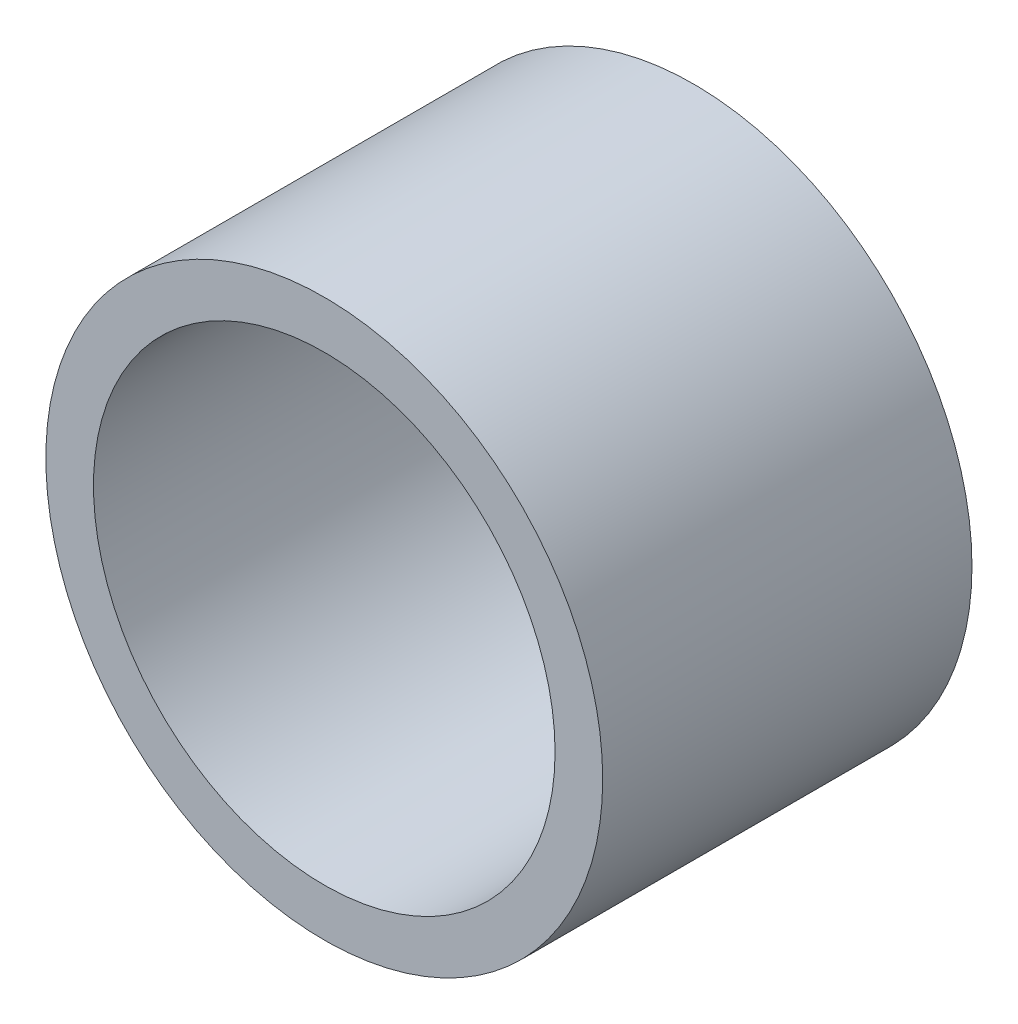
SolidWorks part; units mm, degrees
material "Plain Carbon Steel"
ref_plane "Front Plane" through (0, 0, 0) normal (0, 0, 1) x (1, 0, 0)
ref_plane "Top Plane" through (0, 0, 0) normal (0, 1, 0) x (1, 0, 0)
ref_plane "Right Plane" through (0, 0, 0) normal (1, 0, 0) x (0, 0, -1)
sketch "Sketch1" plane through (0, 0, 0) normal (0, 0, 1) x (1, 0, 0)
  circle A0 centre (0, 0) radius 4.7879
  circle A1 centre (0, 0) radius 3.9688
  dimension "D1" = 9.5758
  dimension "ID" = 7.9375
extrude "Extrude1" add sketch "Sketch1" along normal mid plane 6.35
sketch "Sketch2" plane through (0, 0, 0) normal (1, 0, 0) x (0, 0, -1)
  line L0 (-3.175, -3.9688) -> (3.175, -3.9688) construction
  line L3 (3.175, 3.9688) -> (-3.175, 3.9688) construction
  line L5 (-3.175, -3.9688) -> (3.175, -3.9688)
  line L6 (3.175, 3.9688) -> (-3.175, 3.9688)
sketch "Sketch4" plane through (0, 0, 3.175) normal (0, 0, 1) x (1, 0, 0)
  line L0 (0, 0) -> (-2.8063, 2.8063)
  line L1 (0, -15.7442) -> (0, 15.7442) construction
  circle A0 centre (0, 0) radius 3.9688 construction
  dimension "D1" = 45
